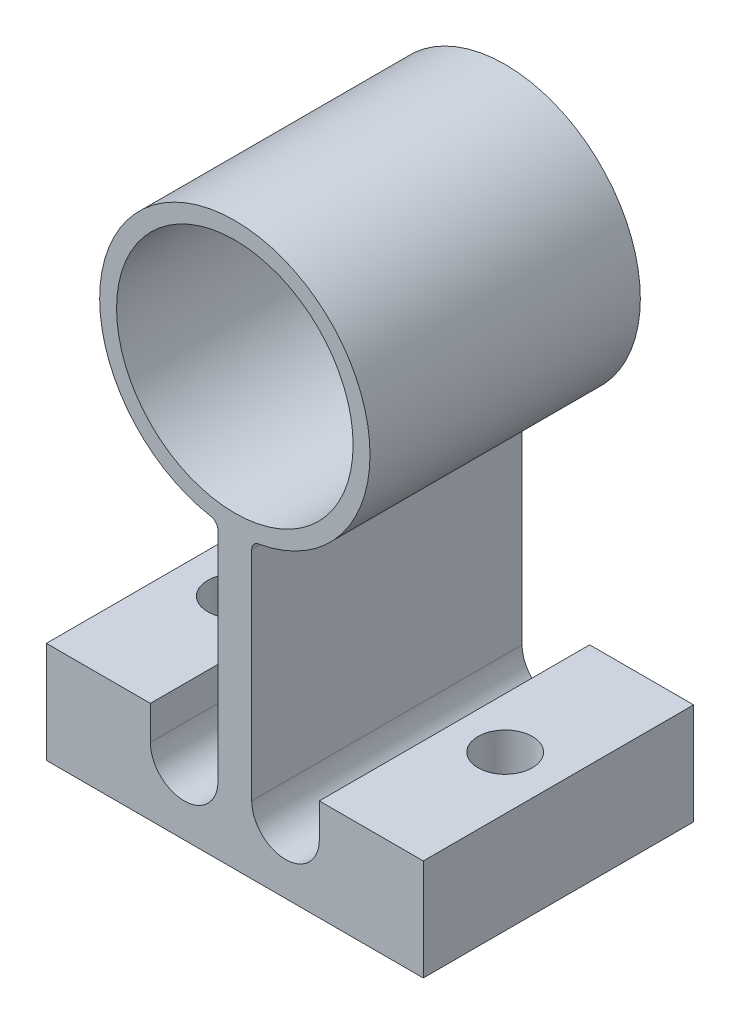
SolidWorks part; units mm, degrees
material "6061 Alloy"
ref_plane "Front Plane" through (0, 0, 0) normal (0, 0, 1) x (1, 0, 0)
ref_plane "Top Plane" through (0, 0, 0) normal (0, 1, 0) x (1, 0, 0)
ref_plane "Right Plane" through (0, 0, 0) normal (1, 0, 0) x (0, 0, -1)
sketch "Sketch1" plane through (0, 0, 0) normal (0, 0, -1) x (1, 0, 0)
  line L0 (0, 0) -> (0, 40.0837) construction
  line L1 (-17.706, 40.0837) -> (17.706, 40.0837)
  line L2 (17.706, 40.0837) -> (17.706, 30.5587)
  line L3 (17.706, 30.5587) -> (1.5875, 30.5587)
  line L4 (1.5875, 12.6004) -> (1.5875, 30.5587)
  line L5 (-1.5875, 12.6004) -> (-1.5875, 30.5587)
  line L6 (-17.706, 30.5587) -> (-1.5875, 30.5587)
  line L7 (-17.706, 40.0837) -> (-17.706, 30.5587)
  arc A0 (-1.5875, 12.6004) -> (1.5875, 12.6004) centre (0, 0) ccw
  circle A1 centre (0, 0) radius 11.1125
  dimension "D2" = 25.4
  dimension "D3" = 22.225
  dimension "D1" = 40.0837
  dimension "D4" = 35.4119
  dimension "D5" = 3.175
  dimension "D6" = 9.525
extrude "Extrude1" add sketch "Sketch1" along normal mid plane 25.4
fillet "Bushing-side fillets" radius 0.7937 2 edges at (1.5875, -12.6004, 0) (-1.5875, -12.6004, 0)
fillet "Mount-side fillets" radius 0.7937 2 edges at (1.5875, -30.5587, 0) (-1.5875, -30.5587, 0)
hole_wizard "1/4 Mounting holes" positions "Sketch3" profile "Sketch2" tap size "1/4-20" standard "Ansi Inch"
sketch "Sketch3" plane through (0, -40.0837, 0) normal (0, -1, 0) x (1, 0, 0)
  line L0 (0, -12.7) -> (0, 12.7) construction
  line L1 (17.706, -12.7) -> (-17.706, -12.7) construction
  line L2 (17.706, 12.7) -> (-17.706, 12.7) construction
  point P0 (-12.7, 0)
  point P12 (12.7, 0)
  dimension "D1" = 25.4
sketch "Sketch2" plane through (-12.7, -40.0837, 0) normal (1, 0, 0) x (0, 0, -1)
  line L0 (0, 0) -> (0, 20.5838)
  line L1 (0, 20.5838) -> (2.5527, 19.05)
  line L2 (2.5527, 19.05) -> (2.5527, 0)
  line L5 (2.5527, 0) -> (0, 0)
  line L10 (0, 20.5838) -> (-2.5527, 19.05) construction
  line L11 (0, -6.35) -> (0, 107.95) construction
  dimension "Tap Drill Dia." = 5.1054
  dimension "Tap Drill Depth" = 19.05
  dimension "Drill Angle" = 118
cosmetic thread "Hole Thread1" parameters "D1"=12.7, "D2"=6.35
cosmetic thread "Hole Thread2" parameters "D1"=12.7, "D2"=6.35
sketch "Sketch4" plane through (0, 0, -12.7) normal (0, 0, -1) x (-1, 0, 0)
  line L0 (1.5875, -29.7649) -> (1.5875, -33.7337)
  line L1 (7.9375, -33.7337) -> (7.9375, -30.5587)
  line L2 (17.706, -30.5587) -> (2.3812, -30.5587) construction
  line L3 (7.9375, -30.5587) -> (2.3812, -30.5587)
  line L4 (-17.706, -40.0837) -> (17.706, -40.0837) construction
  line L5 (0, 0) -> (0, -40.0837) construction
  line L6 (-7.9375, -30.5587) -> (-2.3812, -30.5587)
  line L7 (-7.9375, -33.7337) -> (-7.9375, -30.5587)
  line L8 (-1.5875, -29.7649) -> (-1.5875, -33.7337)
  arc A0 (1.5875, -33.7337) -> (7.9375, -33.7337) centre (4.7625, -33.7337) ccw
  arc A1 (1.5875, -29.7649) -> (2.3812, -30.5587) centre (2.3812, -29.7649) ccw construction
  arc A2 (1.5875, -29.7649) -> (2.3812, -30.5587) centre (2.3812, -29.7649) ccw
  circle A3 centre (4.7625, -33.7337) radius 3.175 construction
  circle A4 centre (-4.7625, -33.7337) radius 3.175 construction
  arc A5 (-1.5875, -29.7649) -> (-2.3812, -30.5587) centre (-2.3812, -29.7649) cw
  arc A6 (-1.5875, -33.7337) -> (-7.9375, -33.7337) centre (-4.7625, -33.7337) cw
  point P11 (4.7625, -36.9087)
  point P24 (-4.7625, -36.9087)
  dimension "D1" = 6.35
  dimension "D2" = 3.175
extrude "Extrude2" cut sketch "Sketch4" against normal through all
